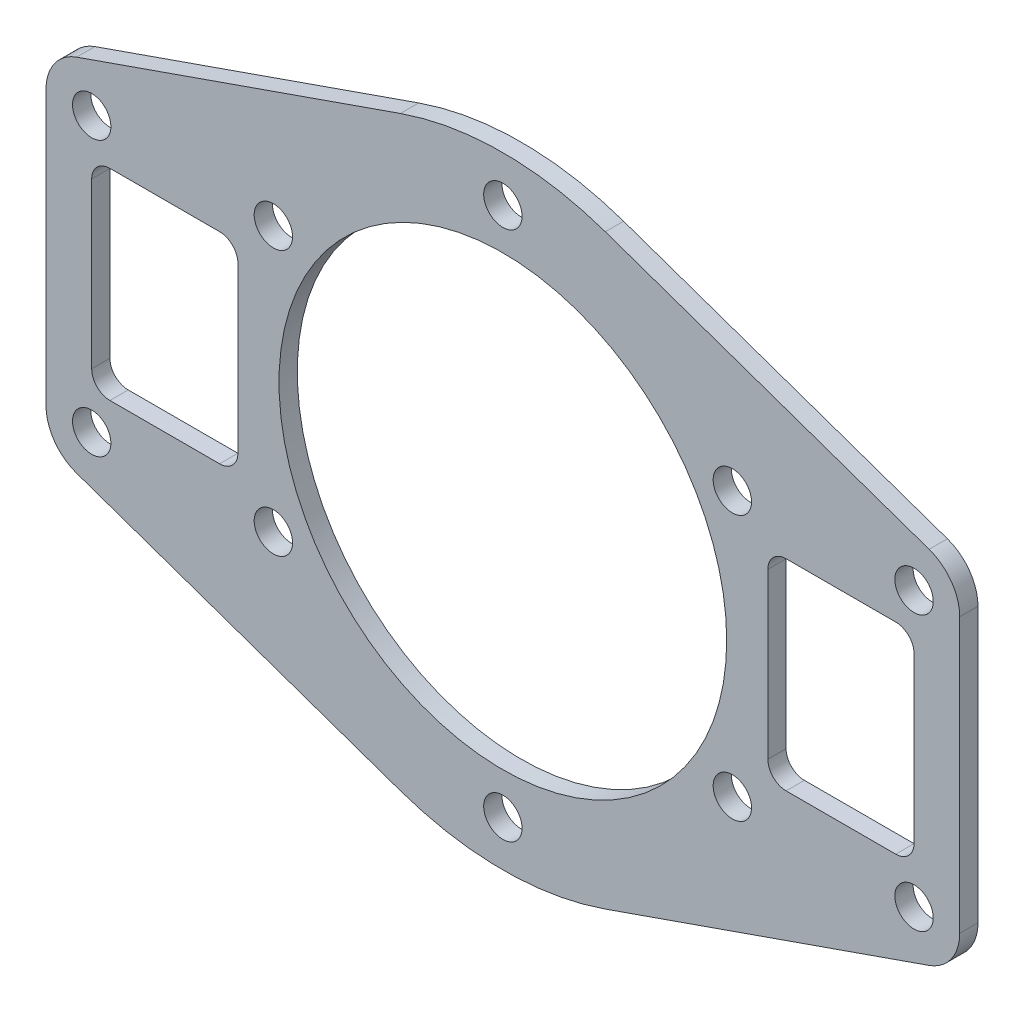
SolidWorks part; units mm, degrees
material "Thornel Mat VMA"
ref_plane "前视基准面" through (0, 0, 0) normal (0, 0, 1) x (1, 0, 0)
ref_plane "上视基准面" through (0, 0, 0) normal (0, 1, 0) x (1, 0, 0)
ref_plane "右视基准面" through (0, 0, 0) normal (1, 0, 0) x (0, 0, -1)
sketch "草图1" plane through (0, 0, 0) normal (0, 0, 1) x (1, 0, 0)
  line L0 (-50, 15) -> (-50, -15)
  line L1 (45, -15) -> (-45, -15) construction
  line L2 (45, -15) -> (45, 15) construction
  line L3 (45, 15) -> (-45, 15) construction
  line L4 (-45, -15) -> (-45, 15) construction
  line L5 (45, -15) -> (-45, 15) construction
  line L6 (45, 15) -> (-45, -15) construction
  line L7 (-46.6488, -19.7203) -> (-11.2117, -32.0983)
  line L8 (11.2117, -32.0983) -> (46.6488, -19.7203)
  line L9 (50, -15) -> (50, 15)
  line L10 (46.6488, 19.7203) -> (11.2117, 32.0983)
  line L11 (-11.2117, 32.0983) -> (-46.6488, 19.7203)
  circle A0 centre (0, 0) radius 24.5
  circle A1 centre (0, 0) radius 29 construction
  circle A2 centre (0, 29) radius 2.1
  circle A3 centre (25.1147, 14.5) radius 2.1
  circle A4 centre (25.1147, -14.5) radius 2.1
  circle A5 centre (0, -29) radius 2.1
  circle A6 centre (-25.1147, -14.5) radius 2.1
  circle A7 centre (-25.1147, 14.5) radius 2.1
  circle A8 centre (-45, 15) radius 2.1
  circle A9 centre (-45, -15) radius 2.1
  circle A10 centre (45, -15) radius 2.1
  circle A11 centre (45, 15) radius 2.1
  arc A12 (-11.2117, -32.0983) -> (11.2117, -32.0983) centre (0, 0) ccw
  arc A13 (11.2117, 32.0983) -> (-11.2117, 32.0983) centre (0, 0) ccw
  arc A14 (50, 15) -> (46.6488, 19.7203) centre (45, 15) ccw
  arc A15 (46.6488, -19.7203) -> (50, -15) centre (45, -15) ccw
  arc A16 (-50, -15) -> (-46.6488, -19.7203) centre (-45, -15) ccw
  arc A17 (-50, 15) -> (-46.6488, 19.7203) centre (-45, 15) cw
  point P18 (0, 0)
  dimension "D1" = 49
  dimension "D2" = 58
  dimension "D3" = 4.2
  dimension "D5" = 4.2
  dimension "D8" = 34
  dimension "D9" = 5
  dimension "D6" = 30
  dimension "D7" = 90
  dimension "D4" = 6
extrude "凸台-拉伸1" add sketch "草图1" along normal blind 2
sketch "草图2" plane through (0, 0, 2) normal (0, 0, 1) x (1, 0, 0)
  line L0 (29, 0) -> (-29, 0) construction
  line L1 (-43, 11) -> (-31, 11)
  line L2 (-45, 9) -> (-45, -9)
  line L3 (-43, -11) -> (-31, -11)
  line L4 (-29, 9) -> (-29, -9)
  line L5 (31, 11) -> (43, 11)
  line L6 (29, 9) -> (29, -9)
  line L7 (31, -11) -> (43, -11)
  line L8 (45, 9) -> (45, -9)
  line L9 (-50, 15) -> (-50, -15) construction
  arc A0 (43, 11) -> (45, 9) centre (43, 9) cw
  arc A1 (29, -9) -> (31, -11) centre (31, -9) ccw
  arc A2 (43, -11) -> (45, -9) centre (43, -9) ccw
  arc A3 (31, 11) -> (29, 9) centre (31, 9) ccw
  arc A4 (-31, 11) -> (-29, 9) centre (-31, 9) cw
  arc A5 (-45, -9) -> (-43, -11) centre (-43, -9) ccw
  arc A6 (-31, -11) -> (-29, -9) centre (-31, -9) ccw
  arc A7 (-43, 11) -> (-45, 9) centre (-43, 9) ccw
  point P25 (-45, -11)
  point P30 (-45, 11)
  dimension "D4" = 2
  dimension "D5" = 2
  dimension "D1" = 58
  dimension "D2" = 5
  dimension "D3" = 22
extrude "切除-拉伸1" cut sketch "草图2" against normal blind 10
